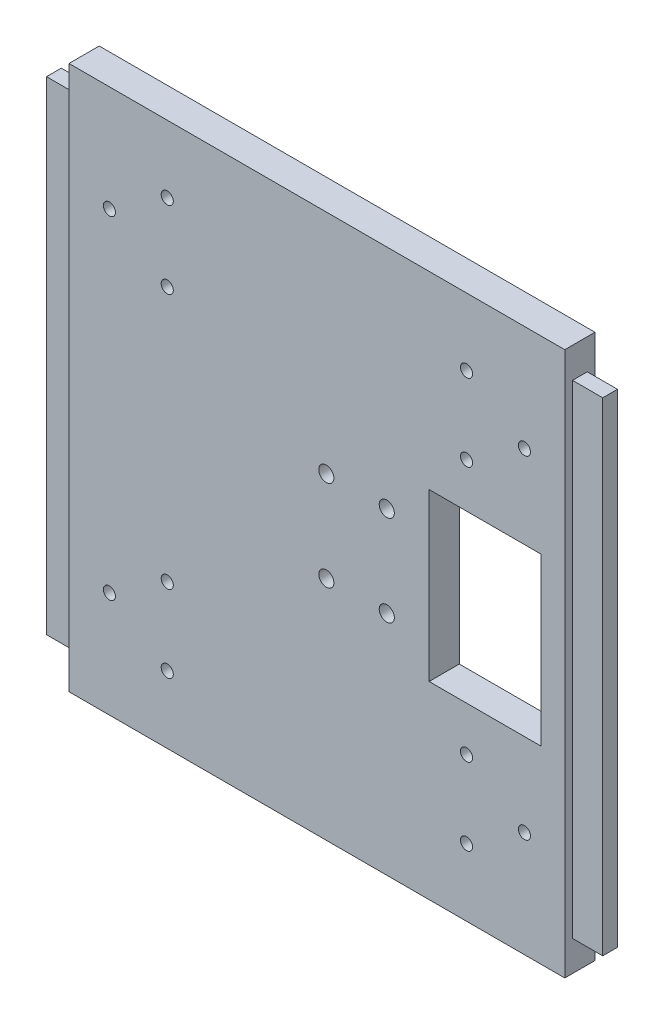
SolidWorks part; units mm, degrees
ref_plane "前视基准面" through (0, 0, 0) normal (0, 0, 1) x (1, 0, 0)
ref_plane "上视基准面" through (0, 0, 0) normal (0, 1, 0) x (1, 0, 0)
ref_plane "右视基准面" through (0, 0, 0) normal (1, 0, 0) x (0, 0, -1)
other "Configuration Table"
sketch "草图1" plane through (0, 0, 0) normal (0, 0, 1) x (1, 0, 0)
  line L1 (0, 0) -> (164, 0)
  line L2 (0, 0) -> (0, 180)
  line L3 (0, 180) -> (164, 180)
  line L4 (164, 0) -> (164, 180)
  line L5 (0, 0) -> (164, 180) construction
  line L6 (0, 180) -> (164, 0) construction
  point P4 (82, 90)
  dimension "D1" = 164
  dimension "D2" = 180
extrude "凸台-拉伸1" add sketch "草图1" along normal blind 10
sketch "草图2" plane through (0, 0, 0) normal (-1, 0, 0) x (0, 0, 1)
  line L0 (10, 180) -> (10, 0) construction
  line L1 (2.56, 169.94) -> (7.44, 169.94)
  line L2 (2.56, 169.94) -> (2.56, 10.06)
  line L3 (2.56, 10.06) -> (7.44, 10.06)
  line L4 (7.44, 169.94) -> (7.44, 10.06)
  line L5 (2.56, 169.94) -> (7.44, 10.06) construction
  line L6 (2.56, 10.06) -> (7.44, 169.94) construction
  line L7 (10, 180) -> (0, 180) construction
  point P4 (5, 90)
  dimension "D1" = 4.88
  dimension "D2" = 159.88
  dimension "D3" = 5
  dimension "D4" = 90
extrude "凸台-拉伸2" add sketch "草图2" along normal blind 10
ref_plane "基准面1" through (82, 0, 0) normal (1, 0, 0) x (0, 0, -1)
mirror "镜向1" about plane through (82, 0, 0) normal (1, 0, 0) of "凸台-拉伸2"
sketch "草图3" plane through (0, 0, 0) normal (0, 0, -1) x (-1, 0, 0)
  line L0 (-164, 169.94) -> (-164, 10.06) construction
  line L1 (-164, 90) -> (12.5762, 90) construction
  line L2 (-174, 169.94) -> (-174, 10.06) construction
  line L3 (-164, 0) -> (-164, 180) construction
  line L4 (0, 169.94) -> (0, 10.06) construction
  line L5 (0, 180) -> (0, 0) construction
  circle A0 centre (-150.6426, 145) radius 2
  circle A1 centre (-131.5, 157.75) radius 2
  circle A2 centre (-131.5, 132.25) radius 2
  circle A3 centre (-13.3574, 145) radius 2
  circle A4 centre (-32.5, 157.75) radius 2
  circle A5 centre (-32.5, 132.25) radius 2
  circle A6 centre (-131.5, 47.75) radius 2
  circle A7 centre (-131.5, 22.25) radius 2
  circle A8 centre (-150.6426, 35) radius 2
  circle A9 centre (-32.5, 47.75) radius 2
  circle A10 centre (-32.5, 22.25) radius 2
  circle A11 centre (-13.3574, 35) radius 2
  dimension "D1" = 4
  dimension "D2" = 4
  dimension "D3" = 4
  dimension "D4" = 4
  dimension "D5" = 4
  dimension "D6" = 4
  dimension "D7" = 23
  dimension "D8" = 23
  dimension "D9" = 25.5
  dimension "D10" = 10
  dimension "D11" = 55
  dimension "D12" = 32.5
  dimension "D13" = 25.5
  dimension "D14" = 23
  dimension "D15" = 23
  dimension "D16" = 32.5
  dimension "D17" = 32.5
  dimension "D18" = 55
  dimension "D19" = 32.5
extrude "切除-拉伸1" cut sketch "草图3" against normal blind 10
sketch "草图5" plane through (0, 0, 10) normal (0, 0, 1) x (1, 0, 0)
  line L0 (0, 90) -> (164, 90) construction
  line L1 (85.1179, 105) -> (85.1179, 75) construction
  line L3 (0, 10.06) -> (0, 169.94) construction
  line L4 (5, 110.5) -> (125, 110.5) construction
  line L5 (5, 110.5) -> (5, 69.5) construction
  line L6 (5, 69.5) -> (125, 69.5) construction
  line L7 (125, 110.5) -> (125, 69.5) construction
  line L8 (5, 110.5) -> (125, 69.5) construction
  line L9 (5, 69.5) -> (125, 110.5) construction
  line L10 (119.1179, 117.5) -> (156.1179, 117.5)
  line L11 (75.1179, 110) -> (118.1179, 110) construction
  line L12 (75.1179, 110) -> (75.1179, 70) construction
  line L13 (75.1179, 70) -> (118.1179, 70) construction
  line L14 (118.1179, 110) -> (118.1179, 70) construction
  line L15 (75.1179, 110) -> (118.1179, 70) construction
  line L16 (75.1179, 70) -> (118.1179, 110) construction
  line L17 (119.1179, 117.5) -> (119.1179, 62.5)
  line L18 (119.1179, 62.5) -> (156.1179, 62.5)
  line L19 (156.1179, 117.5) -> (156.1179, 62.5)
  line L20 (119.1179, 117.5) -> (156.1179, 62.5) construction
  line L21 (119.1179, 62.5) -> (156.1179, 117.5) construction
  circle A1 centre (85.1179, 105) radius 2.5
  circle A2 centre (85.1179, 75) radius 2.5
  circle A5 centre (105.1179, 105) radius 2.5
  circle A6 centre (105.1179, 75) radius 2.5
  point P5 (65, 90)
  point P13 (96.6179, 90)
  point P22 (85.1179, 90)
  point P27 (137.6179, 90)
  dimension "D5" = 43
  dimension "D7" = 5
  dimension "D8" = 2
  dimension "D9" = 5
  dimension "D10" = 55
  dimension "D1" = 120
  dimension "D2" = 41
  dimension "D3" = 5
  dimension "D4" = 6.8821
  dimension "D6" = 40
  dimension "D11" = 30
  dimension "D12" = 10
  dimension "D13" = 37
  dimension "D14" = 2
extrude "切除-拉伸3" cut sketch "草图5" against normal blind 8
sketch "草图6" plane through (0, 0, 2) normal (0, 0, 1) x (1, 0, 0)
  line L4 (119.1179, 117.5) -> (119.1179, 62.5)
  line L5 (119.1179, 62.5) -> (156.1179, 62.5)
  line L6 (156.1179, 62.5) -> (156.1179, 117.5)
  line L7 (156.1179, 117.5) -> (119.1179, 117.5)
  line L8 (119.1179, 117.5) -> (119.1179, 62.5)
  line L9 (119.1179, 62.5) -> (156.1179, 62.5)
  line L10 (156.1179, 62.5) -> (156.1179, 117.5)
  line L11 (156.1179, 117.5) -> (119.1179, 117.5)
  dimension "D1" = 0
extrude "切除-拉伸4" cut sketch "草图6" against normal blind 8
